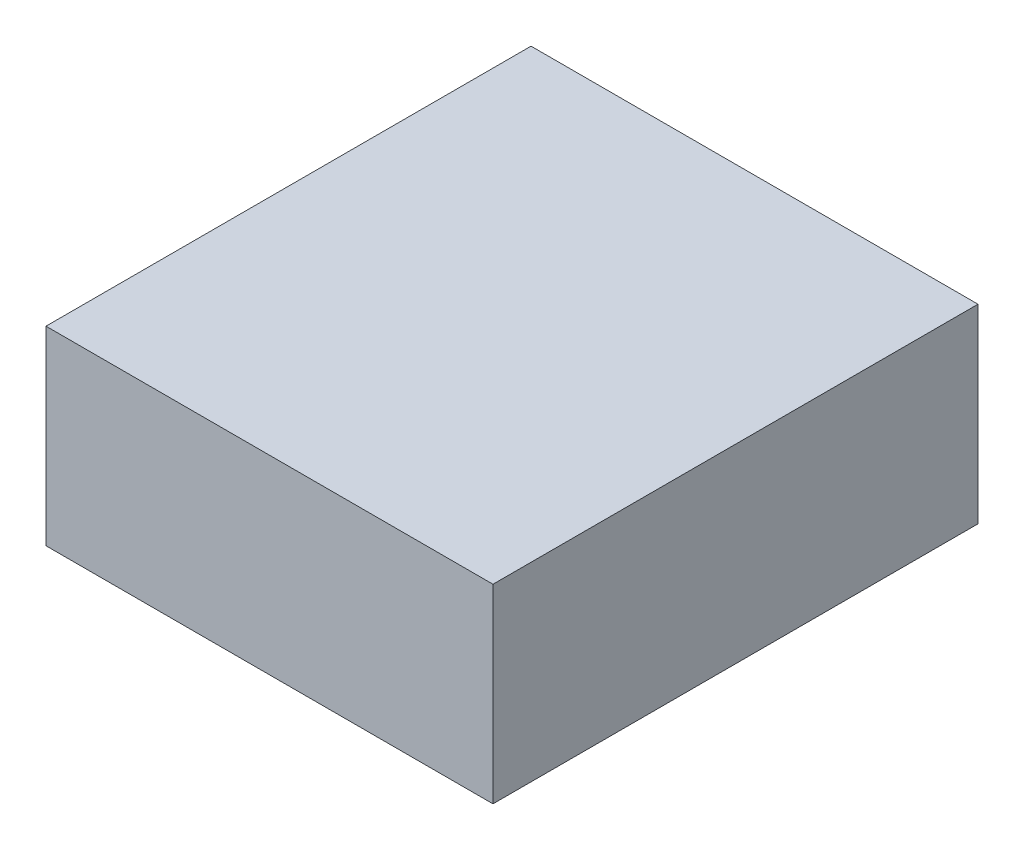
SolidWorks part; units mm, degrees
ref_plane "Front Plane" through (0, 0, 0) normal (0, 0, 1) x (1, 0, 0)
ref_plane "Top Plane" through (0, 0, 0) normal (0, 1, 0) x (1, 0, 0)
ref_plane "Right Plane" through (0, 0, 0) normal (1, 0, 0) x (0, 0, -1)
sketch "Sketch1" plane through (0, 0, 0) normal (0, 1, 0) x (1, 0, 0)
  line L1 (-23.5, -25.5) -> (23.5, -25.5)
  line L2 (-23.5, -25.5) -> (-23.5, 25.5)
  line L3 (-23.5, 25.5) -> (23.5, 25.5)
  line L4 (23.5, -25.5) -> (23.5, 25.5)
  line L5 (-23.5, -25.5) -> (23.5, 25.5) construction
  line L6 (-23.5, 25.5) -> (23.5, -25.5) construction
  point P0 (0, 0)
  dimension "D1" = 47
  dimension "D2" = 51
extrude "Boss-Extrude1" add sketch "Sketch1" along normal blind 20
